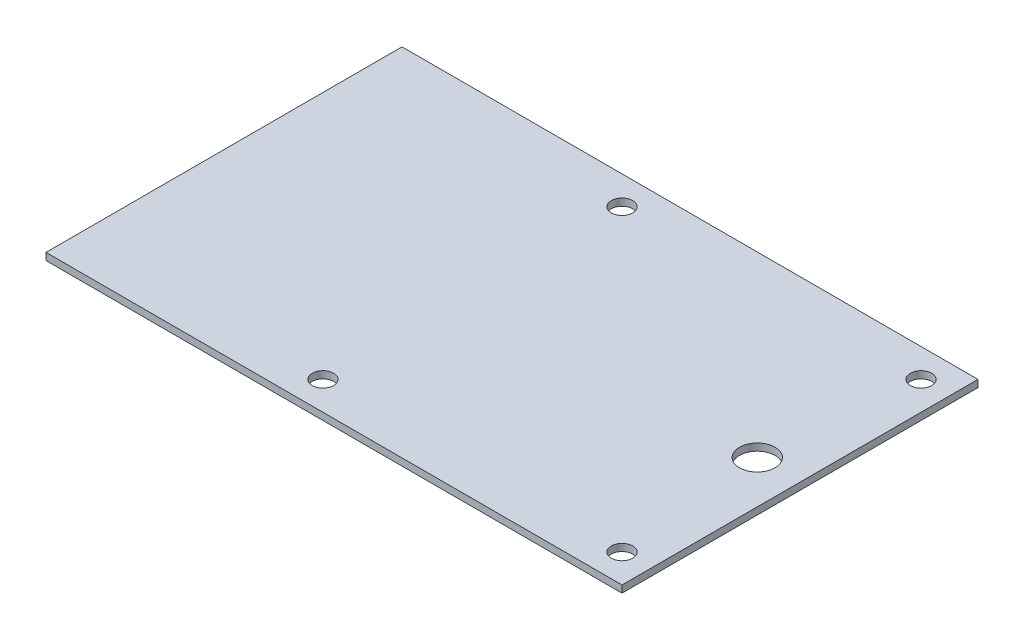
SolidWorks part; units mm, degrees
ref_plane "Plano frontal" through (0, 0, 0) normal (0, 0, 1) x (1, 0, 0)
ref_plane "Plano superior" through (0, 0, 0) normal (0, 1, 0) x (1, 0, 0)
ref_plane "Plano direito" through (0, 0, 0) normal (1, 0, 0) x (0, 0, -1)
sketch "Esboço1" plane through (0, 0, 0) normal (0, 1, 0) x (1, 0, 0)
  line L1 (-40.45, -25) -> (40.45, -25)
  line L2 (-40.45, -25) -> (-40.45, 25)
  line L3 (-40.45, 25) -> (40.45, 25)
  line L4 (40.45, -25) -> (40.45, 25)
  line L5 (-40.45, -25) -> (40.45, 25) construction
  line L6 (-40.45, 25) -> (40.45, -25) construction
  point P0 (0, 0)
  dimension "D1" = 50
  dimension "D2" = 80.9
extrude "Ressalto-extrusão1" add sketch "Esboço1" along normal blind 1
sketch "Esboço2" plane through (0, 1, 0) normal (0, 1, 0) x (1, 0, 0)
  line L0 (40.45, -25) -> (40.45, 25) construction
  line L1 (40.45, 25) -> (-40.45, 25) construction
  line L2 (-40.45, -25) -> (40.45, -25) construction
  circle A0 centre (36.45, 21) radius 1.5
  circle A1 centre (36.45, -21) radius 1.5
  circle A2 centre (-5.55, -21) radius 1.5
  circle A3 centre (-5.55, 21) radius 1.5
  circle A4 centre (34.45, 0) radius 2.5
  dimension "D1" = 4
  dimension "D2" = 4
  dimension "D3" = 4
  dimension "D9" = 6
  dimension "D4" = 46
  dimension "D5" = 4
  dimension "D6" = 46
  dimension "D7" = 4
  dimension "D8" = 4
extrude "Corte-extrusão1" cut sketch "Esboço2" against normal through all
